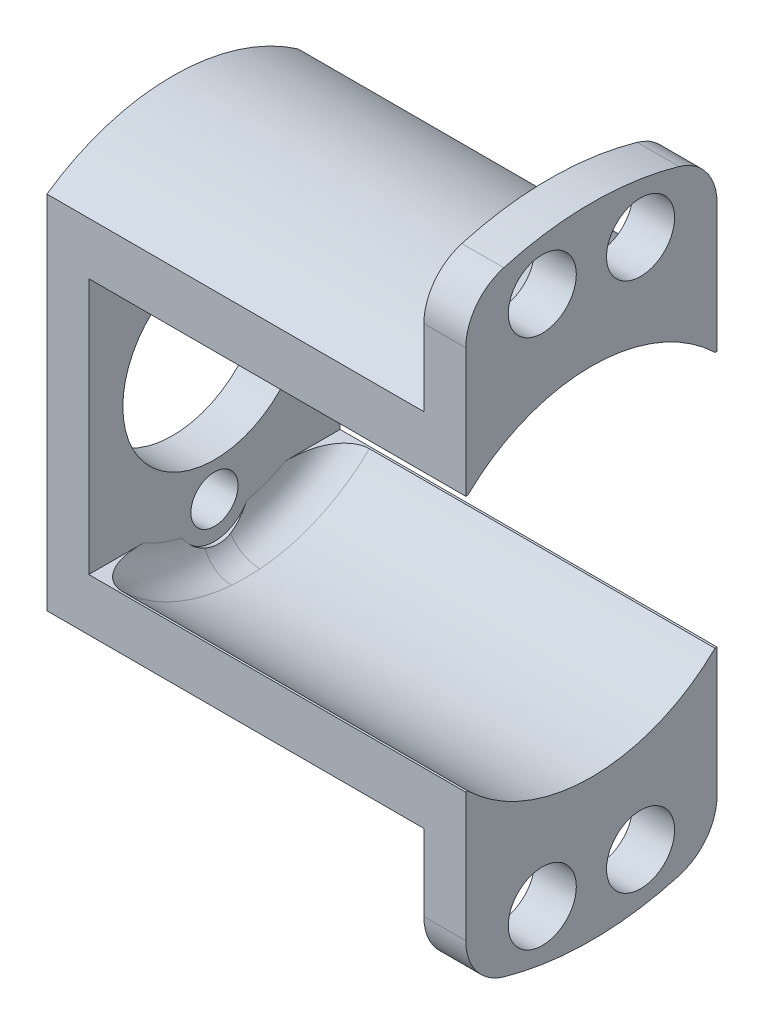
SolidWorks part; units mm, degrees
ref_plane "Front Plane" through (0, 0, 0) normal (0, 0, 1) x (1, 0, 0)
ref_plane "Top Plane" through (0, 0, 0) normal (0, 1, 0) x (1, 0, 0)
ref_plane "Right Plane" through (0, 0, 0) normal (1, 0, 0) x (0, 0, -1)
sketch "Sketch1" plane through (0, 0, 0) normal (0, 0, 1) x (1, 0, 0)
  line L0 (0, 8.75) -> (0, 21)
  line L1 (0, 21) -> (36, 21)
  line L2 (36, 21) -> (36, 22)
  line L3 (36, 22) -> (40, 22)
  line L4 (40, 22) -> (40, 17)
  line L5 (40, 17) -> (4, 17)
  line L6 (4, 17) -> (4, 8.75)
  line L7 (4, 8.75) -> (0, 8.75)
  line L8 (0, 8.75) -> (0, 0) construction
  line L9 (0, 0) -> (40, 0) construction
  line L10 (40, 0) -> (40, 17) construction
  line L11 (0, 14.5) -> (4, 14.5) construction
  dimension "D1" = 8.75
  dimension "D2" = 21
  dimension "D3" = 14.5
  dimension "D4" = 4
  dimension "D5" = 4
  dimension "D6" = 40
  dimension "D7" = 4
  dimension "D8" = 5
revolve "Revolve1" add sketch "Sketch1" angle 360 about L9
sketch "Sketch2" plane through (40, 0, 0) normal (1, 0, 0) x (0, 0, -1)
  line L0 (0, 0) -> (0, 31.8345) construction
  line L4 (0, 25.3188) -> (-4.6926, 25.3188) construction
  line L5 (0, 25.3188) -> (4.6926, 25.3188) construction
  line L6 (12, 28.0401) -> (12, 18.4391)
  line L7 (-12, 28.0401) -> (-12, 18.4391)
  line L8 (12, 18.4391) -> (0, 18.4391) construction
  line L9 (0, 18.4391) -> (-12, 18.4391) construction
  circle A3 centre (0, 0) radius 22 construction
  circle A5 centre (-4.6926, 25.3188) radius 3.25
  arc A6 (12, 18.4391) -> (-12, 18.4391) centre (0, 0) ccw
  circle A7 centre (4.6926, 25.3188) radius 3.25
  circle A8 centre (-4.6926, 25.3188) radius 3.5 construction
  arc A11 (12, 28.0401) -> (-12, 28.0401) centre (0, 0) ccw
  circle A12 centre (0, 0) radius 22 construction
  circle A15 centre (4.6926, 25.3188) radius 4.75 construction
  circle A17 centre (0, 0) radius 21 construction
  dimension "D1" = 30.5
  dimension "D2" = 6.5
  dimension "D5" = 7
  dimension "D4" = 24
extrude "Boss-Extrude1" add sketch "Sketch2" against normal up to surface (4 mm away)
pattern_circular "CirPattern2" count 2 over 360 about axis through (0, 0, 0) along (1, 0, 0) of "Boss-Extrude1"
sketch "Sketch6" plane through (36, 0, 0) normal (-1, 0, 0) x (0, 0, 1)
  line L0 (-12, 28.0401) -> (-12, -28.0401)
  line L1 (-12, -28.0401) -> (-24.7905, -28.0401)
  line L2 (-24.7905, -28.0401) -> (-24.7905, 28.0401)
  line L3 (-24.7905, 28.0401) -> (-12, 28.0401)
  line L4 (12, 28.0401) -> (12, -28.0401)
  line L5 (12, -28.0401) -> (25.1317, -28.0401)
  line L6 (25.1317, -28.0401) -> (25.1317, 28.0401)
  line L7 (25.1317, 28.0401) -> (12, 28.0401)
extrude "Cut-Extrude4" cut sketch "Sketch6" against normal through all both and the other way through all
sketch "Sketch7" plane through (0, 0, 12) normal (0, 0, 1) x (1, 0, 0)
  line L0 (40, 0) -> (40, 12.2337)
  line L1 (40, 28.0401) -> (40, 12.0416) construction
  line L2 (40, 12.2337) -> (4, 12.2337)
  line L3 (4, 12.2337) -> (4, -12.2337)
  line L4 (4, -12.2337) -> (40, -12.2337)
  line L5 (40, -28.0401) -> (40, -12.0416) construction
  line L6 (40, -12.2337) -> (40, 0)
  line L7 (0, 0) -> (40, 0) construction
  line L8 (4, 12.0416) -> (4, -12.0416) construction
  line L9 (0, 17.2337) -> (36, 17.2337) construction
  dimension "D1" = 5
extrude "Cut-Extrude5" cut sketch "Sketch7" against normal through all both and the other way through all
sketch "Sketch8" plane through (0, 0, 0) normal (-1, 0, 0) x (0, 0, 1)
  line L0 (0, 12) -> (0, 0) construction
  line L1 (0, 0) -> (0, -12) construction
  circle A0 centre (0, 0) radius 12 construction
  circle A1 centre (0, -12) radius 2.25
  circle A2 centre (0, 12) radius 2.25
  dimension "D1" = 24
  dimension "D2" = 4.5
extrude "Cut-Extrude6" cut sketch "Sketch8" against normal blind 10
fillet "Fillet1" radius 3 2 edges at (4, -17, 0) (4, 17, 0)
sketch "Sketch9" plane through (4, 0, 0) normal (1, 0, 0) x (0, 0, -1)
  circle A0 centre (0, 12) radius 3.5
  circle A1 centre (0, -12) radius 3.5
  dimension "D1" = 7
extrude "Cut-Extrude7" cut sketch "Sketch9" along normal blind 30
fillet "Fillet2" radius 5 4 edges at (38, 28.0401, -12) (38, 28.0401, 12) (38, -28.0401, 12) (38, -28.0401, -12)
